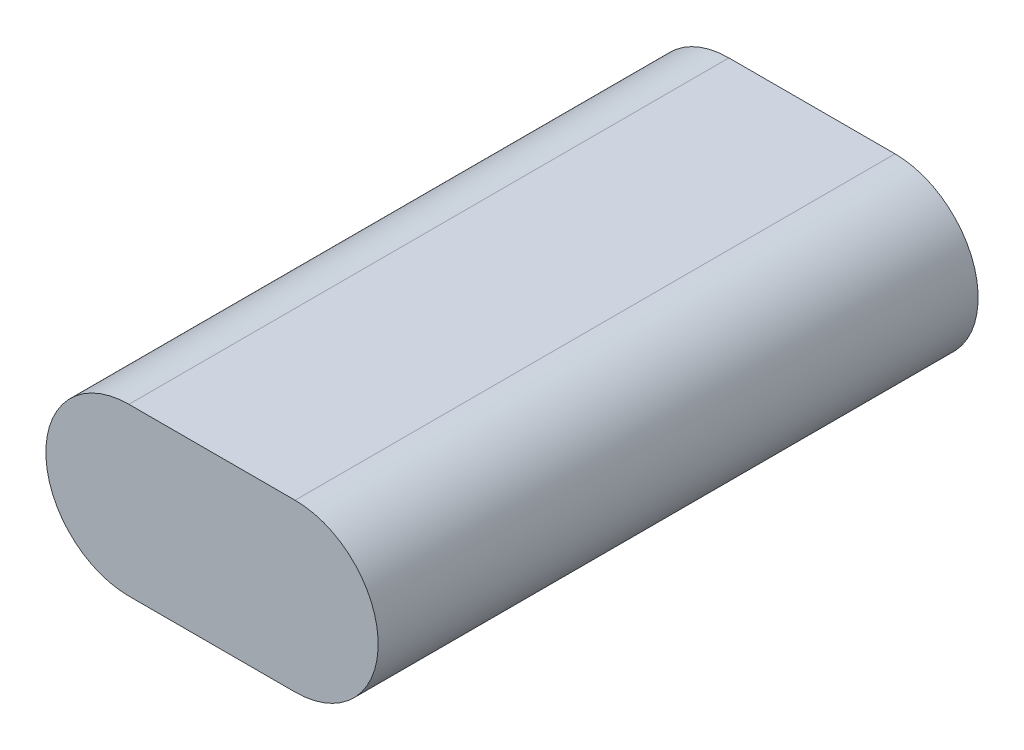
SolidWorks part; units mm, degrees
ref_plane "Piano frontale" through (0, 0, 0) normal (0, 0, 1) x (1, 0, 0)
ref_plane "Piano superiore" through (0, 0, 0) normal (0, 1, 0) x (1, 0, 0)
ref_plane "Piano destro" through (0, 0, 0) normal (1, 0, 0) x (0, 0, -1)
sketch "Schizzo1" plane through (0, 0, 0) normal (0, 0, 1) x (1, 0, 0)
  line L0 (0, 9) -> (18, 9)
  line L1 (0, -9) -> (18, -9)
  circle A0 centre (0, 0) radius 9
  circle A1 centre (18, 0) radius 9
  dimension "D1" = 18
  dimension "D2" = 18
  dimension "D3" = 18
extrude "Estrusione-Estrusione1" add sketch "Schizzo1" along normal blind 65 contours A1 | A0 | A1 L0 A0 | A1 A0 L1
